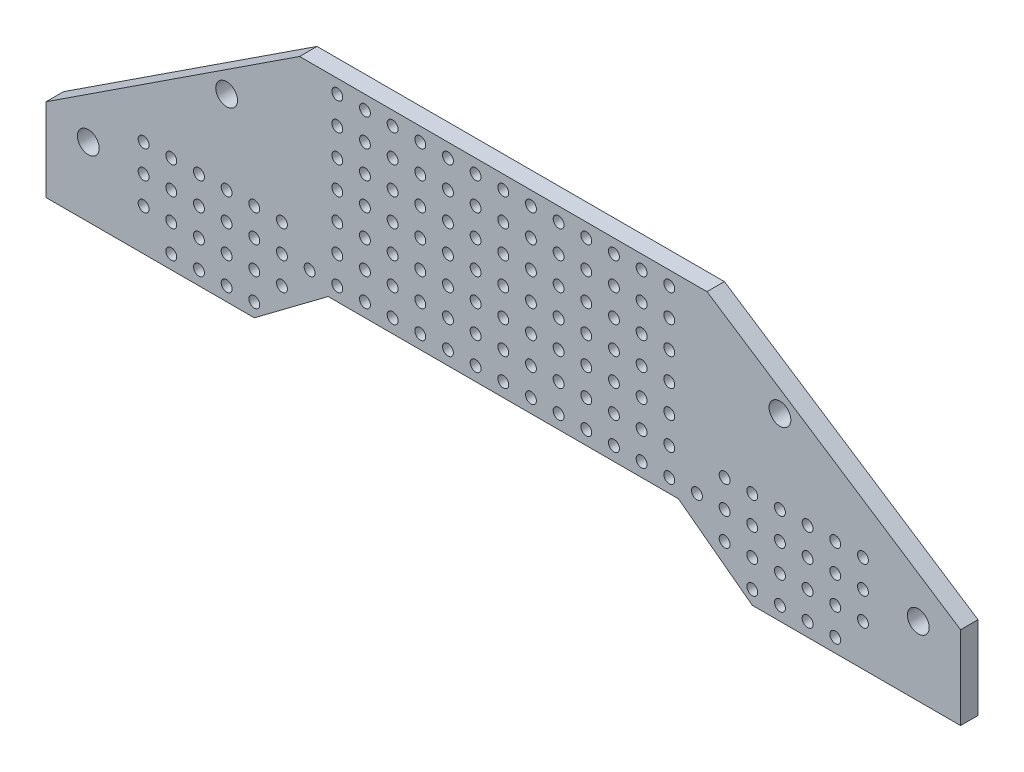
SolidWorks part; units mm, degrees
ref_plane "Front Plane" through (0, 0, 0) normal (0, 0, 1) x (1, 0, 0)
ref_plane "Top Plane" through (0, 0, 0) normal (0, 1, 0) x (1, 0, 0)
ref_plane "Right Plane" through (0, 0, 0) normal (1, 0, 0) x (0, 0, -1)
sketch "Sketch1" plane through (0, 0, 0) normal (0, 0, 1) x (1, 0, 0)
  line L0 (-16.0813, 0) -> (16.0813, 0)
  line L1 (16.0813, 0) -> (22.86, -5.08)
  line L2 (22.86, -5.08) -> (41.9828, -5.08)
  line L3 (41.9828, -5.08) -> (41.9828, 2.54)
  line L4 (41.9828, 2.54) -> (18.7, 17.78)
  line L5 (18.7, 17.78) -> (-18.7, 17.78)
  line L6 (0, 17.78) -> (0, 0) construction
  line L7 (-41.9828, 2.54) -> (-18.7, 17.78)
  line L8 (-41.9828, -5.08) -> (-41.9828, 2.54)
  line L9 (-22.86, -5.08) -> (-41.9828, -5.08)
  line L10 (-16.0813, 0) -> (-22.86, -5.08)
  line L11 (-38.1, 1.27) -> (-33.02, 1.27) construction
  circle A0 centre (0, 1.27) radius 0.5
  circle A1 centre (2.54, 1.27) radius 0.5
  circle A2 centre (5.08, 1.27) radius 0.5
  circle A3 centre (7.62, 1.27) radius 0.5
  circle A4 centre (10.16, 1.27) radius 0.5
  circle A5 centre (12.7, 1.27) radius 0.5
  circle A6 centre (15.24, 1.27) radius 0.5
  circle A7 centre (17.78, 1.27) radius 0.5
  circle A8 centre (20.32, 1.27) radius 0.5
  circle A9 centre (22.86, 1.27) radius 0.5
  circle A10 centre (25.4, 1.27) radius 0.5
  circle A11 centre (27.94, 1.27) radius 0.5
  circle A12 centre (30.48, 1.27) radius 0.5
  circle A13 centre (33.02, 1.27) radius 0.5
  circle A15 centre (20.32, 3.81) radius 0.5
  circle A16 centre (22.86, 3.81) radius 0.5
  circle A17 centre (25.4, 3.81) radius 0.5
  circle A18 centre (27.94, 3.81) radius 0.5
  circle A19 centre (30.48, 3.81) radius 0.5
  circle A20 centre (33.02, 3.81) radius 0.5
  circle A21 centre (20.32, -1.27) radius 0.5
  circle A22 centre (22.86, -1.27) radius 0.5
  circle A23 centre (25.4, -1.27) radius 0.5
  circle A24 centre (27.94, -1.27) radius 0.5
  circle A25 centre (30.48, -1.27) radius 0.5
  circle A26 centre (33.02, -1.27) radius 0.5
  circle A27 centre (0, 3.81) radius 0.5
  circle A28 centre (2.54, 3.81) radius 0.5
  circle A29 centre (5.08, 3.81) radius 0.5
  circle A30 centre (7.62, 3.81) radius 0.5
  circle A31 centre (10.16, 3.81) radius 0.5
  circle A32 centre (12.7, 3.81) radius 0.5
  circle A33 centre (15.24, 3.81) radius 0.5
  circle A34 centre (0, 6.35) radius 0.5
  circle A35 centre (2.54, 6.35) radius 0.5
  circle A36 centre (5.08, 6.35) radius 0.5
  circle A37 centre (7.62, 6.35) radius 0.5
  circle A38 centre (10.16, 6.35) radius 0.5
  circle A39 centre (12.7, 6.35) radius 0.5
  circle A40 centre (15.24, 6.35) radius 0.5
  circle A41 centre (0, 8.89) radius 0.5
  circle A42 centre (2.54, 8.89) radius 0.5
  circle A43 centre (5.08, 8.89) radius 0.5
  circle A44 centre (7.62, 8.89) radius 0.5
  circle A45 centre (10.16, 8.89) radius 0.5
  circle A46 centre (12.7, 8.89) radius 0.5
  circle A47 centre (15.24, 8.89) radius 0.5
  circle A48 centre (0, 11.43) radius 0.5
  circle A49 centre (2.54, 11.43) radius 0.5
  circle A50 centre (5.08, 11.43) radius 0.5
  circle A51 centre (7.62, 11.43) radius 0.5
  circle A52 centre (10.16, 11.43) radius 0.5
  circle A53 centre (12.7, 11.43) radius 0.5
  circle A54 centre (15.24, 11.43) radius 0.5
  circle A55 centre (0, 13.97) radius 0.5
  circle A56 centre (2.54, 13.97) radius 0.5
  circle A57 centre (5.08, 13.97) radius 0.5
  circle A58 centre (7.62, 13.97) radius 0.5
  circle A59 centre (10.16, 13.97) radius 0.5
  circle A60 centre (12.7, 13.97) radius 0.5
  circle A61 centre (15.24, 13.97) radius 0.5
  circle A62 centre (0, 16.51) radius 0.5
  circle A63 centre (2.54, 16.51) radius 0.5
  circle A64 centre (5.08, 16.51) radius 0.5
  circle A65 centre (7.62, 16.51) radius 0.5
  circle A66 centre (10.16, 16.51) radius 0.5
  circle A67 centre (12.7, 16.51) radius 0.5
  circle A68 centre (15.24, 16.51) radius 0.5
  circle A69 centre (22.86, -3.81) radius 0.5
  circle A70 centre (25.4, -3.81) radius 0.5
  circle A71 centre (27.94, -3.81) radius 0.5
  circle A72 centre (30.48, -3.81) radius 0.5
  circle A73 centre (-30.48, -3.81) radius 0.5
  circle A74 centre (-27.94, -3.81) radius 0.5
  circle A75 centre (-25.4, -3.81) radius 0.5
  circle A76 centre (-22.86, -3.81) radius 0.5
  circle A77 centre (-15.24, 16.51) radius 0.5
  circle A78 centre (-12.7, 16.51) radius 0.5
  circle A79 centre (-10.16, 16.51) radius 0.5
  circle A80 centre (-7.62, 16.51) radius 0.5
  circle A81 centre (-5.08, 16.51) radius 0.5
  circle A82 centre (-2.54, 16.51) radius 0.5
  circle A83 centre (-15.24, 13.97) radius 0.5
  circle A84 centre (-12.7, 13.97) radius 0.5
  circle A85 centre (-10.16, 13.97) radius 0.5
  circle A86 centre (-7.62, 13.97) radius 0.5
  circle A87 centre (-5.08, 13.97) radius 0.5
  circle A88 centre (-2.54, 13.97) radius 0.5
  circle A89 centre (-15.24, 11.43) radius 0.5
  circle A90 centre (-12.7, 11.43) radius 0.5
  circle A91 centre (-10.16, 11.43) radius 0.5
  circle A92 centre (-7.62, 11.43) radius 0.5
  circle A93 centre (-5.08, 11.43) radius 0.5
  circle A94 centre (-2.54, 11.43) radius 0.5
  circle A95 centre (-15.24, 8.89) radius 0.5
  circle A96 centre (-12.7, 8.89) radius 0.5
  circle A97 centre (-10.16, 8.89) radius 0.5
  circle A98 centre (-7.62, 8.89) radius 0.5
  circle A99 centre (-5.08, 8.89) radius 0.5
  circle A100 centre (-2.54, 8.89) radius 0.5
  circle A101 centre (-15.24, 6.35) radius 0.5
  circle A102 centre (-12.7, 6.35) radius 0.5
  circle A103 centre (-10.16, 6.35) radius 0.5
  circle A104 centre (-7.62, 6.35) radius 0.5
  circle A105 centre (-5.08, 6.35) radius 0.5
  circle A106 centre (-2.54, 6.35) radius 0.5
  circle A107 centre (-15.24, 3.81) radius 0.5
  circle A108 centre (-12.7, 3.81) radius 0.5
  circle A109 centre (-10.16, 3.81) radius 0.5
  circle A110 centre (-7.62, 3.81) radius 0.5
  circle A111 centre (-5.08, 3.81) radius 0.5
  circle A112 centre (-2.54, 3.81) radius 0.5
  circle A113 centre (-33.02, -1.27) radius 0.5
  circle A114 centre (-30.48, -1.27) radius 0.5
  circle A115 centre (-27.94, -1.27) radius 0.5
  circle A116 centre (-25.4, -1.27) radius 0.5
  circle A117 centre (-22.86, -1.27) radius 0.5
  circle A118 centre (-20.32, -1.27) radius 0.5
  circle A119 centre (-33.02, 3.81) radius 0.5
  circle A120 centre (-30.48, 3.81) radius 0.5
  circle A121 centre (-27.94, 3.81) radius 0.5
  circle A122 centre (-25.4, 3.81) radius 0.5
  circle A123 centre (-22.86, 3.81) radius 0.5
  circle A124 centre (-20.32, 3.81) radius 0.5
  circle A125 centre (-33.02, 1.27) radius 0.5
  circle A126 centre (-30.48, 1.27) radius 0.5
  circle A127 centre (-27.94, 1.27) radius 0.5
  circle A128 centre (-25.4, 1.27) radius 0.5
  circle A129 centre (-22.86, 1.27) radius 0.5
  circle A130 centre (-20.32, 1.27) radius 0.5
  circle A131 centre (-17.78, 1.27) radius 0.5
  circle A132 centre (-15.24, 1.27) radius 0.5
  circle A133 centre (-12.7, 1.27) radius 0.5
  circle A134 centre (-10.16, 1.27) radius 0.5
  circle A135 centre (-7.62, 1.27) radius 0.5
  circle A136 centre (-5.08, 1.27) radius 0.5
  circle A137 centre (-2.54, 1.27) radius 0.5
  circle A138 centre (-38.1, 1.27) radius 1
  circle A139 centre (38.1, 1.27) radius 1
  circle A140 centre (25.4, 11.43) radius 1
  circle A141 centre (-25.4, 11.43) radius 1
  point P293 (25.4, 9.5645)
  point P294 (0, 0)
  point P295 (17.78, 17.78)
  point P296 (18.7184, 17.78)
  dimension "D1" = 1
  dimension "D11" = 2
  dimension "D14" = 2
  dimension "D6" = 1.27
  dimension "D7" = 1.27
  dimension "D9" = 1.27
  dimension "D10" = 5.08
  dimension "D12" = 7.62
  dimension "D13" = 2.54
  dimension "D15" = 37.4
  dimension "D16" = 7.62
  dimension "D2" = 14
  dimension "D3" = 2
  dimension "D4" = 2
  dimension "D5" = 7
  dimension "D8" = 2
extrude "Boss-Extrude1" add sketch "Sketch1" along normal blind 1.6
